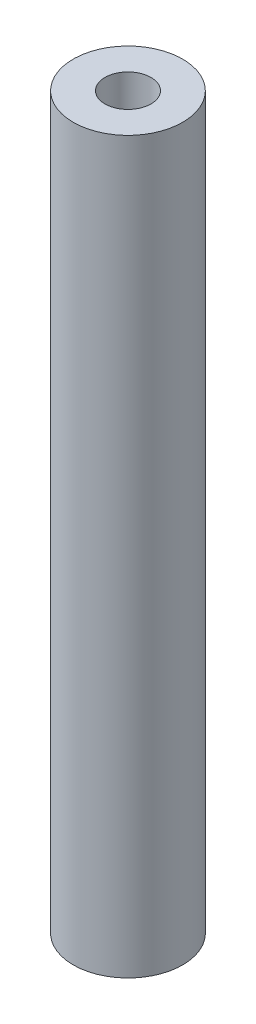
SolidWorks part; units mm, degrees
ref_plane "Front Plane" through (0, 0, 0) normal (0, 0, 1) x (1, 0, 0)
ref_plane "Top Plane" through (0, 0, 0) normal (0, 1, 0) x (1, 0, 0)
ref_plane "Right Plane" through (0, 0, 0) normal (1, 0, 0) x (0, 0, -1)
sketch "Sketch1" plane through (0, 0, 0) normal (0, 1, 0) x (1, 0, 0)
  circle A0 centre (0, 0) radius 1.45
  circle A1 centre (0, 0) radius 3.45
  dimension "D1" = 2.9
  dimension "D2" = 6.9
extrude "Boss-Extrude1" add sketch "Sketch1" along normal blind 46
